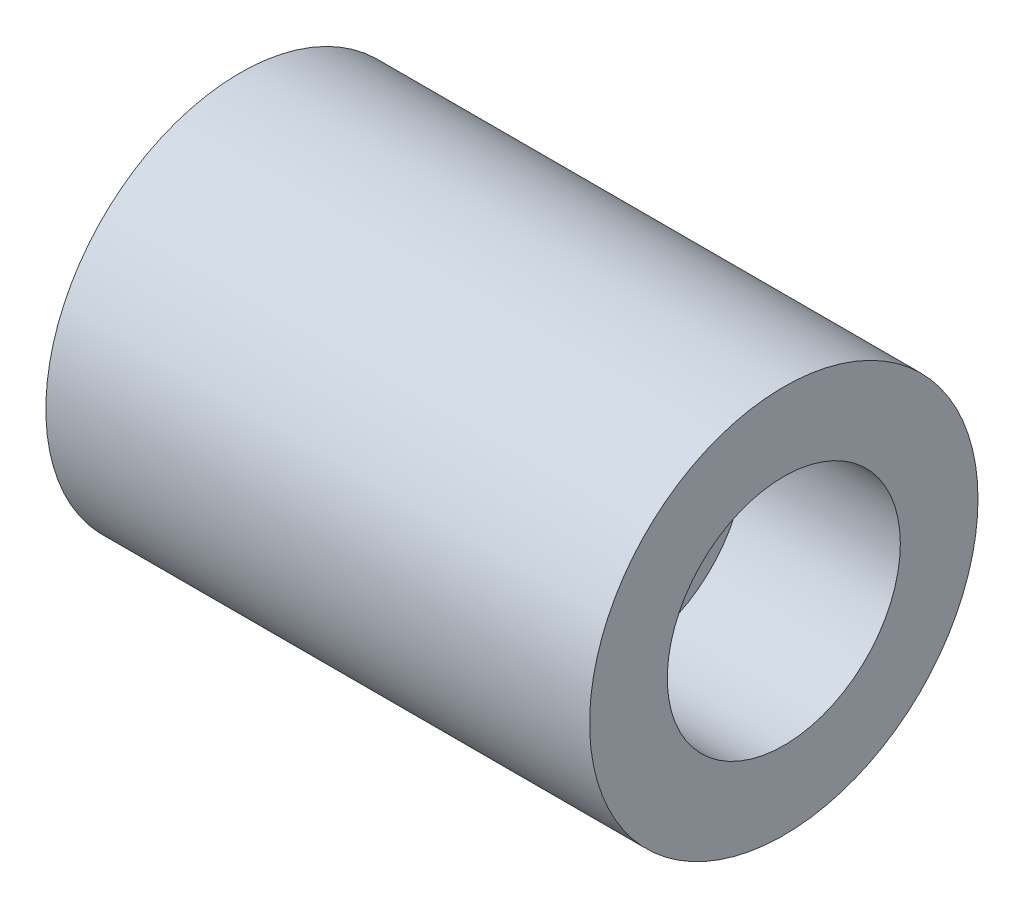
SolidWorks part; units mm, degrees
ref_plane "Alzado" through (0, 0, 0) normal (0, 0, 1) x (1, 0, 0)
ref_plane "Planta" through (0, 0, 0) normal (0, 1, 0) x (1, 0, 0)
ref_plane "Vista lateral" through (0, 0, 0) normal (1, 0, 0) x (0, 0, -1)
sketch "Croquis1" plane through (0, 0, 0) normal (0, 0, 1) x (1, 0, 0)
  line L0 (0, 0) -> (0, 50)
  line L1 (0, 50) -> (140, 50)
  line L2 (140, 50) -> (140, 30)
  line L3 (140, 30) -> (100, 30)
  line L4 (100, 30) -> (100, 10)
  line L5 (100, 10) -> (20, 10)
  line L6 (20, 10) -> (20, 0)
  line L7 (20, 0) -> (0, 0)
  dimension "D1" = 10
  dimension "D2" = 30
  dimension "D3" = 50
  dimension "D4" = 140
  dimension "D5" = 40
  dimension "D6" = 120
revolve "Revolución1" add sketch "Croquis1" angle 360 about L7
equation "\"A\" = 10mm"
equation "\"B\" = 20mm"
equation "\"C\" = 70mm"
equation "\"D1@Croquis1\"=\"A\""
equation "\"D2@Croquis1\"=\"A\"+\"B\""
equation "\"D3@Croquis1\"=(\"A\"+\"B\"+\"C\")/2"
equation "\"D4@Croquis1\"=\"C\"*2"
equation "\"D5@Croquis1\"=\"B\"*2"
equation "\"D6@Croquis1\"=4*(\"A\"+\"B\")"
